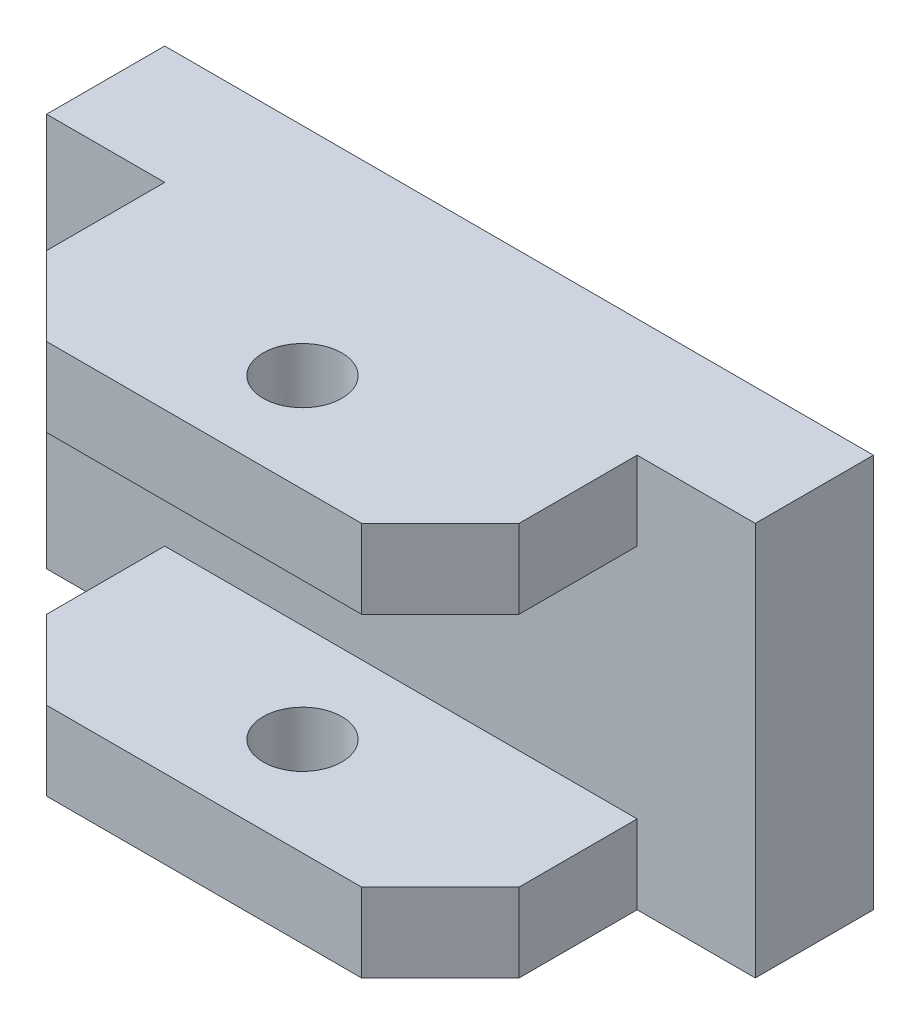
SolidWorks part; units mm, degrees
ref_plane "Front Plane" through (0, 0, 0) normal (0, 0, 1) x (1, 0, 0)
ref_plane "Top Plane" through (0, 0, 0) normal (0, 1, 0) x (1, 0, 0)
ref_plane "Right Plane" through (0, 0, 0) normal (1, 0, 0) x (0, 0, -1)
sketch "Sketch3" plane through (0, 0, 0) normal (0, 0, 1) x (1, 0, 0)
  line L1 (-45, -25) -> (45, -25)
  line L2 (-45, -25) -> (-45, 25)
  line L3 (-45, 25) -> (45, 25)
  line L4 (45, -25) -> (45, 25)
  line L5 (-45, -25) -> (45, 25) construction
  line L6 (-45, 25) -> (45, -25) construction
  point P0 (0, 0)
  dimension "D1" = 90
  dimension "D2" = 50
extrude "Boss-Extrude4" add sketch "Sketch3" along normal blind 15
sketch "Sketch4" plane through (0, 0, 15) normal (0, 0, 1) x (1, 0, 0)
  line L0 (45, 25) -> (-45, 25) construction
  line L1 (-30, 25) -> (30, 25)
  line L2 (-30, 25) -> (-30, 15)
  line L3 (-30, 15) -> (30, 15)
  line L4 (30, 25) -> (30, 15)
  line L5 (-45, 25) -> (-45, -25) construction
  line L7 (-30, -25) -> (-30, -15)
  line L8 (-45, -25) -> (45, -25) construction
  line L9 (-30, -15) -> (30, -15)
  line L10 (30, -15) -> (30, -25)
  line L11 (30, -25) -> (-30, -25)
  dimension "D1" = 60
  dimension "D2" = 10
  dimension "D3" = 15
extrude "Boss-Extrude5" add sketch "Sketch4" along normal blind 25
sketch "Sketch5" plane through (0, -25, 0) normal (0, -1, 0) x (1, 0, 0)
  line L0 (-45, 0) -> (45, 0) construction
  line L1 (30, 40) -> (30, 15) construction
  circle A0 centre (0, 27.5) radius 5
  point P6 (30, 27.5)
  dimension "D1" = 27.5
  dimension "D2" = 30
extrude "Cut-Extrude1" cut sketch "Sketch5" against normal through all
fillet "Fillet1" radius 10 4 edges at (-30, 20, 40) (-30, -20, 40) (30, -20, 40) (30, 20, 40) profile chamfer
